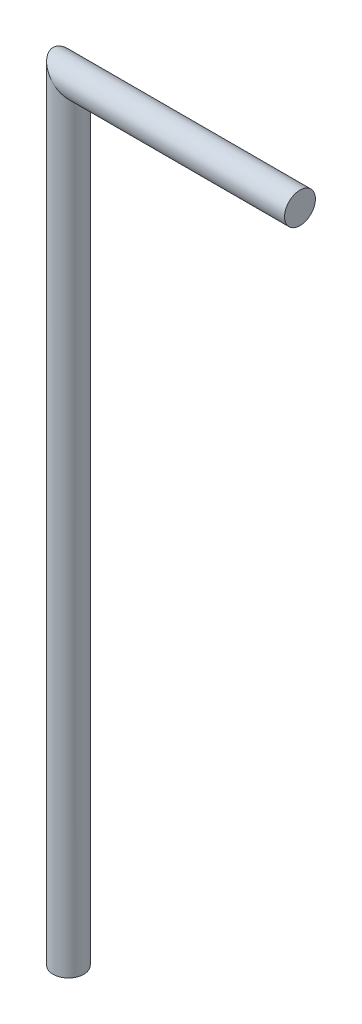
SolidWorks part; units mm, degrees
ref_plane "Front Plane" through (0, 0, 0) normal (0, 0, 1) x (1, 0, 0)
ref_plane "Top Plane" through (0, 0, 0) normal (0, 1, 0) x (1, 0, 0)
ref_plane "Right Plane" through (0, 0, 0) normal (1, 0, 0) x (0, 0, -1)
sketch "Sketch2" plane through (0, 0, 0) normal (0, 0, 1) x (1, 0, 0)
  line L0 (0, 0) -> (0, 50)
  line L1 (0, 50) -> (15, 50)
  dimension "D1" = 50
  dimension "D2" = 15
sketch "Sketch3" plane through (0, 0, 0) normal (0, 1, 0) x (1, 0, 0)
  circle A0 centre (0, 0) radius 1
  dimension "D1" = 2
sweep "Sweep1" add profiles "Sketch3" path "Sketch2"
